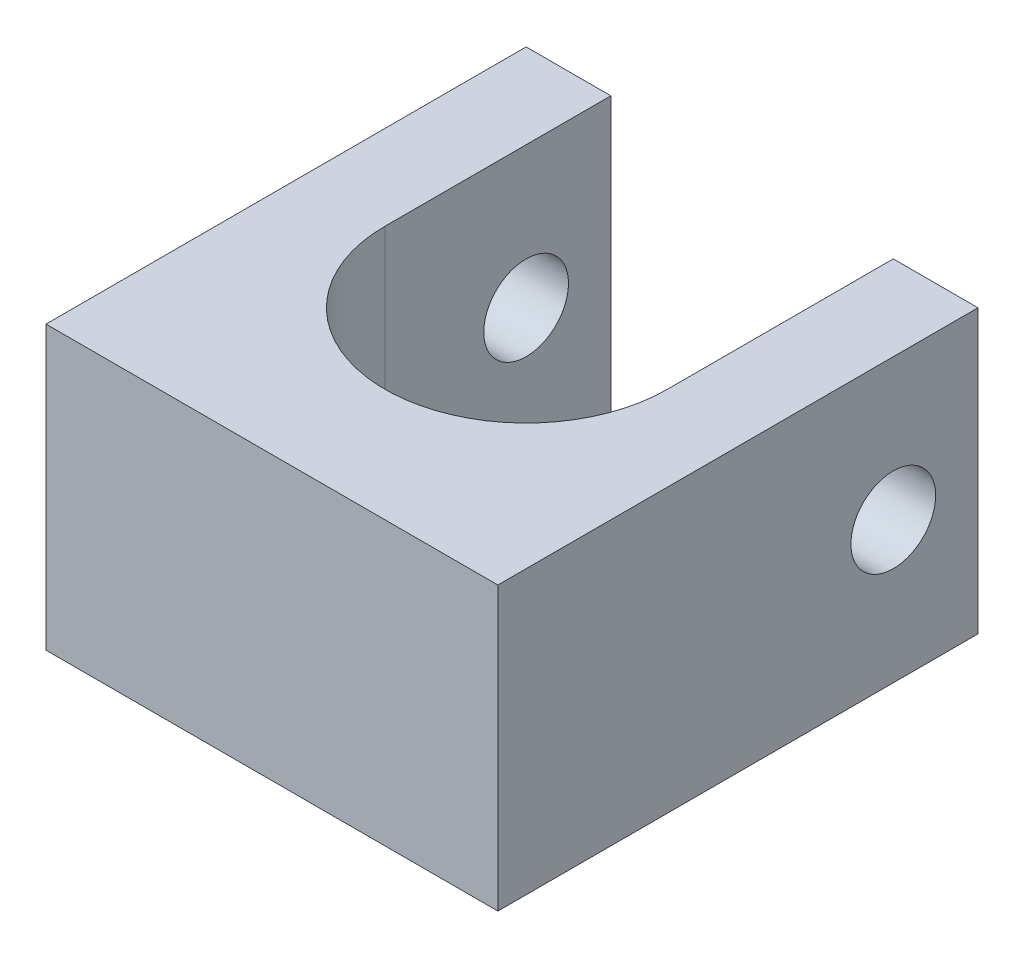
SolidWorks part; units mm, degrees
ref_plane "Front Plane" through (0, 0, 0) normal (0, 0, 1) x (1, 0, 0)
ref_plane "Top Plane" through (0, 0, 0) normal (0, 1, 0) x (1, 0, 0)
ref_plane "Right Plane" through (0, 0, 0) normal (1, 0, 0) x (0, 0, -1)
sketch "Sketch1" plane through (0, 0, 0) normal (0, 0, 1) x (1, 0, 0)
  line L1 (-40, -25) -> (40, -25)
  line L2 (-40, -25) -> (-40, 25)
  line L3 (-40, 25) -> (40, 25)
  line L4 (40, -25) -> (40, 25)
  line L5 (-40, -25) -> (40, 25) construction
  line L6 (-40, 25) -> (40, -25) construction
  point P0 (0, 0)
  dimension "D1" = 80
  dimension "D2" = 50
extrude "Boss-Extrude1" add sketch "Sketch1" along normal blind 85
sketch "Sketch3" plane through (0, 0, 0) normal (0, 0, -1) x (-1, 0, 0)
  line L1 (-25, -27.6448) -> (25, -27.6448)
  line L2 (-25, -27.6448) -> (-25, 27.6448)
  line L3 (-25, 27.6448) -> (25, 27.6448)
  line L4 (25, -27.6448) -> (25, 27.6448)
  line L5 (-25, -27.6448) -> (25, 27.6448) construction
  line L6 (-25, 27.6448) -> (25, -27.6448) construction
  point P0 (0, 0)
  dimension "D1" = 50
extrude "Cut-Extrude1" cut sketch "Sketch3" against normal blind 40
sketch "Sketch4" plane through (40, 0, 0) normal (1, 0, 0) x (0, 0, -1)
  circle A0 centre (-15, 0) radius 7.5
  dimension "D1" = 15
  dimension "D2" = 15
extrude "Cut-Extrude3" cut sketch "Sketch4" against normal through all
sketch "Sketch5" plane through (0, 25, 0) normal (0, 1, 0) x (1, 0, 0)
  line L0 (25, -40) -> (-25, -40) construction
  line L1 (25, -40) -> (-25, -40)
  arc A0 (-25, -40) -> (25, -40) centre (0, -40) ccw
extrude "Cut-Extrude4" cut sketch "Sketch5" against normal through all
